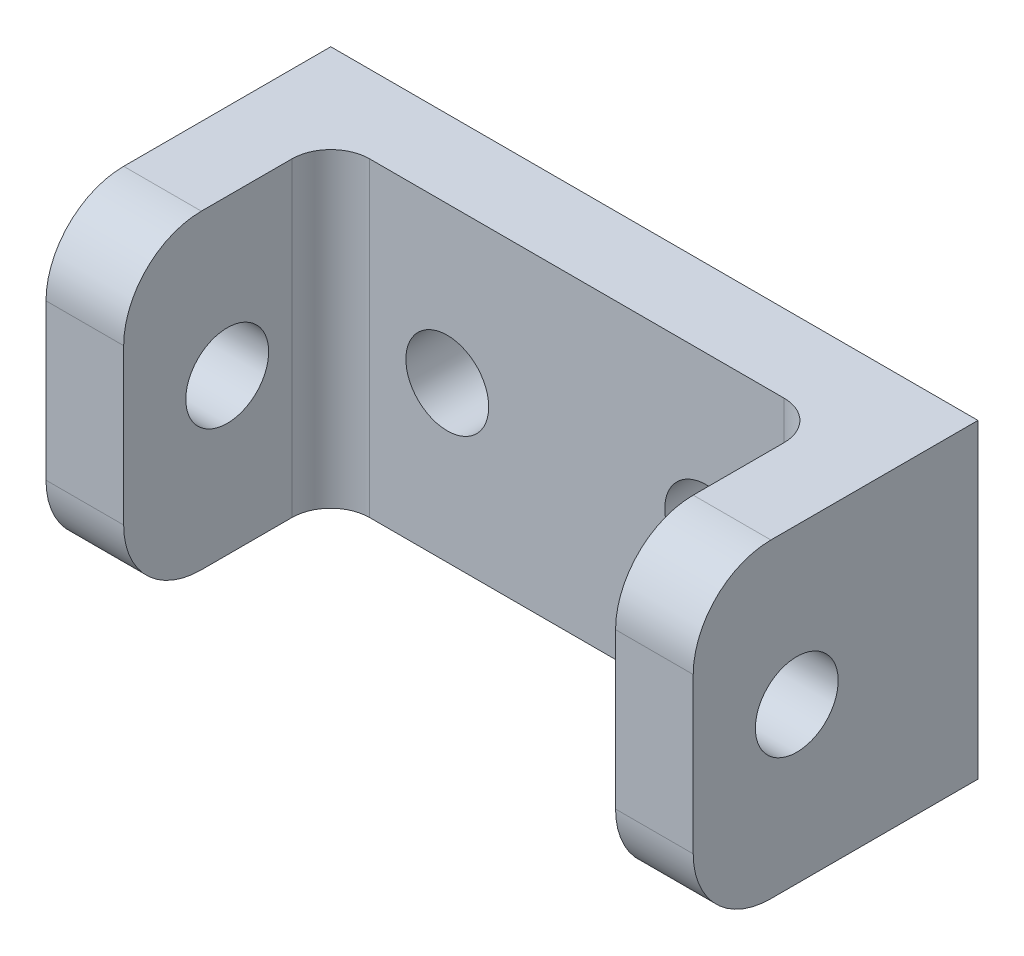
SolidWorks part; units mm, degrees
ref_plane "前视基准面" through (0, 0, 0) normal (0, 0, 1) x (1, 0, 0)
ref_plane "上视基准面" through (0, 0, 0) normal (0, 1, 0) x (1, 0, 0)
ref_plane "右视基准面" through (0, 0, 0) normal (1, 0, 0) x (0, 0, -1)
sketch "草图1" plane through (0, 0, 0) normal (0, 0, 1) x (1, 0, 0)
  line L0 (40, -26.5152) -> (40, 26.5152) construction
  line L1 (12.5, -30) -> (-12.5, -30)
  line L2 (12.5, -30) -> (12.5, -18)
  line L3 (12.5, -18) -> (-12.5, -18)
  line L4 (-12.5, -30) -> (-12.5, -18)
  line L5 (-26.5, -40) -> (26.5, -40) construction
  dimension "D1" = 12
  dimension "D2" = 25
  dimension "D3" = 27.5
  dimension "D4" = 10
extrude "凸台-拉伸1" add sketch "草图1" along normal blind 3
sketch "草图2" plane through (-12.5, 0, 0) normal (-1, 0, 0) x (0, 0, 1)
  line L1 (3, -30) -> (11, -30)
  line L2 (3, -30) -> (3, -18)
  line L3 (3, -18) -> (11, -18)
  line L4 (11, -30) -> (11, -18)
  dimension "D1" = 12
  dimension "D2" = 8
extrude "凸台-拉伸2" add sketch "草图2" against normal blind 3
fillet "圆角1" radius 3 2 edges at (-11, -18, 11) (-11, -30, 11)
fillet "圆角2" radius 1.5 1 edges at (-9.5, -24, 3)
sketch "草图3" plane through (-12.5, 0, 0) normal (-1, 0, 0) x (0, 0, 1)
  line L0 (11, -27) -> (11, -21) construction
  line L1 (8, -30) -> (0, -30) construction
  circle A0 centre (7, -24) radius 1.6
  dimension "D1" = 3.2
  dimension "D2" = 4
  dimension "D3" = 6
extrude "切除-拉伸1" cut sketch "草图3" against normal blind 3
mirror "镜向1" about plane through (0, 0, 0) normal (1, 0, 0) of "凸台-拉伸2", "圆角1", "圆角2", "切除-拉伸1"
sketch "草图4" plane through (0, 0, 3) normal (0, 0, 1) x (1, 0, 0)
  line L0 (-8, -30) -> (8, -30) construction
  line L1 (12.5, -30) -> (12.5, -18) construction
  circle A0 centre (5, -24) radius 1.6
  circle A1 centre (-5, -24) radius 1.6
  dimension "D1" = 3.2
  dimension "D2" = 6
  dimension "D3" = 6
  dimension "D4" = 10
  dimension "D5" = 7.5
extrude "切除-拉伸2" cut sketch "草图4" against normal blind 3
